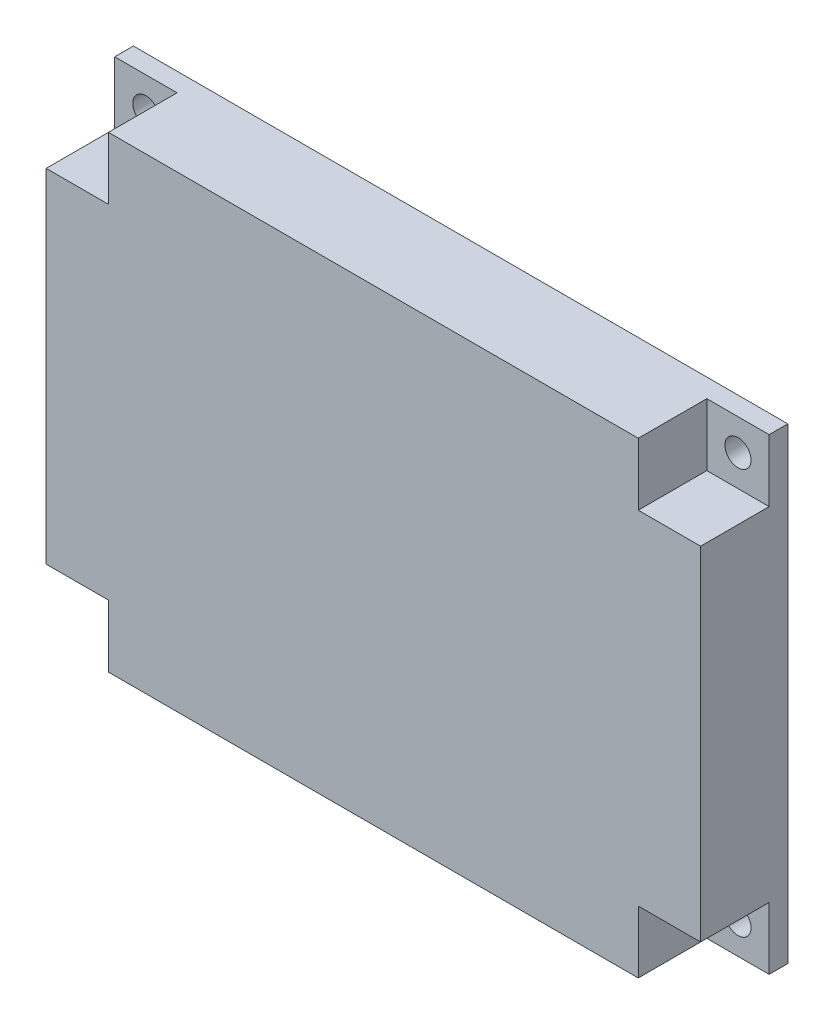
SolidWorks part; units mm, degrees
ref_plane "Plan de face" through (0, 0, 0) normal (0, 0, 1) x (1, 0, 0)
ref_plane "Plan de dessus" through (0, 0, 0) normal (0, 1, 0) x (1, 0, 0)
ref_plane "Plan de droite" through (0, 0, 0) normal (1, 0, 0) x (0, 0, -1)
sketch "Esquisse1" plane through (0, 0, 0) normal (0, 0, 1) x (1, 0, 0)
  line L0 (0, 37.5) -> (0, -37.5) construction
  line L1 (-52.5, 37.5) -> (52.5, 37.5)
  line L2 (-52.5, 37.5) -> (-52.5, -37.5)
  line L3 (-52.5, -37.5) -> (52.5, -37.5)
  line L4 (52.5, 37.5) -> (52.5, -37.5)
  line L5 (52.5, 0) -> (-52.5, 0) construction
  line L6 (47.5, 32.5) -> (-47.5, 32.5) construction
  line L7 (-47.5, 32.5) -> (-47.5, -32.5) construction
  circle A4 centre (47.5, 32.5) radius 2.1
  circle A5 centre (-47.5, 32.5) radius 2.1
  circle A6 centre (47.5, -32.5) radius 2.1
  circle A7 centre (-47.5, -32.5) radius 2.1
  point P0 (0, 0)
  dimension "D3" = 95
  dimension "D5" = 4.2
  dimension "D1" = 105
  dimension "D2" = 75
  dimension "D4" = 65
extrude "Boss.-Extru.1" add sketch "Esquisse1" along normal blind 14
sketch "Esquisse3" plane through (0, 0, 14) normal (0, 0, 1) x (1, 0, 0)
  line L0 (0, 37.5) -> (0, -37.5) construction
  line L1 (42.5, 27.5) -> (52.5, 27.5)
  line L2 (42.5, 27.5) -> (42.5, 37.5)
  line L3 (42.5, 37.5) -> (52.5, 37.5)
  line L4 (52.5, 27.5) -> (52.5, 37.5)
  line L5 (42.5, 27.5) -> (52.5, 37.5) construction
  line L6 (42.5, 37.5) -> (52.5, 27.5) construction
  line L7 (52.5, 37.5) -> (-52.5, 37.5) construction
  line L8 (-52.5, -37.5) -> (52.5, -37.5) construction
  line L9 (52.5, 0) -> (-52.5, 0) construction
  line L10 (52.5, -37.5) -> (52.5, 37.5) construction
  line L11 (-52.5, 37.5) -> (-52.5, -37.5) construction
  line L12 (-42.5, 27.5) -> (-52.5, 27.5)
  line L13 (-52.5, 27.5) -> (-52.5, 37.5)
  line L14 (-42.5, 37.5) -> (-52.5, 37.5)
  line L15 (-42.5, 27.5) -> (-42.5, 37.5)
  line L16 (-42.5, -27.5) -> (-42.5, -37.5)
  line L17 (-42.5, -37.5) -> (-52.5, -37.5)
  line L18 (-52.5, -27.5) -> (-52.5, -37.5)
  line L19 (-42.5, -27.5) -> (-52.5, -27.5)
  line L20 (52.5, -27.5) -> (52.5, -37.5)
  line L21 (42.5, -37.5) -> (52.5, -37.5)
  line L22 (42.5, -27.5) -> (42.5, -37.5)
  line L23 (42.5, -27.5) -> (52.5, -27.5)
  point P0 (47.5, 32.5)
extrude "Enlèv. mat.-Extru.1" cut sketch "Esquisse3" against normal blind 11
